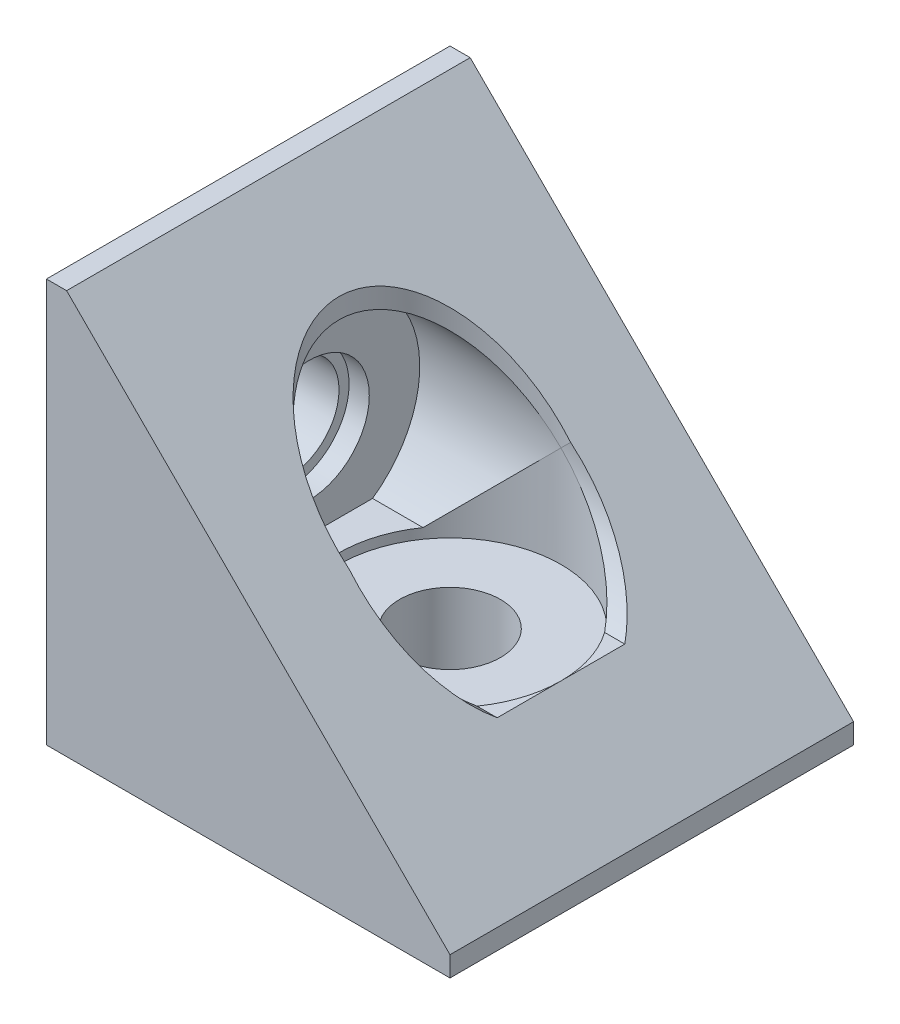
SolidWorks part; units mm, degrees
material "1.4511 (X3CrNb17)"
ref_plane "前视基准面" through (0, 0, 0) normal (0, 0, 1) x (1, 0, 0)
ref_plane "上视基准面" through (0, 0, 0) normal (0, 1, 0) x (1, 0, 0)
ref_plane "右视基准面" through (0, 0, 0) normal (1, 0, 0) x (0, 0, -1)
sketch "草图1" plane through (0, 0, 0) normal (0, 0, 1) x (1, 0, 0)
  line L0 (0, 0) -> (20, 0)
  line L1 (20, 0) -> (20, 1)
  line L2 (20, 1) -> (1, 20)
  line L3 (1, 20) -> (0, 20)
  line L4 (0, 20) -> (0, 0)
  dimension "D1" = 20
  dimension "D2" = 20
  dimension "D3" = 1
  dimension "D4" = 1
extrude "凸台-拉伸1" add sketch "草图1" along normal blind 20
ref_plane "基准面1" through (0, 20, 0) normal (0, 1, 0) x (1, 0, 0)
sketch "草图2" plane through (0, 20, 0) normal (0, 1, 0) x (1, 0, 0)
  line L2 (0, 0) -> (20, -20) construction
  line L3 (20, 0) -> (0, -20) construction
  line L4 (0, -20) -> (0, 0) construction
  line L5 (1, -20) -> (0, -20) construction
  circle A0 centre (10, -10) radius 5.5
  dimension "D1" = 11
extrude "切除-拉伸1" cut sketch "草图2" against normal blind 15
ref_plane "基准面2" through (20, 0, 0) normal (1, 0, 0) x (0, 0, -1)
sketch "草图3" plane through (20, 0, 0) normal (1, 0, 0) x (0, 0, -1)
  line L0 (-20, 20) -> (0, 20) construction
  line L1 (-13.1623, 5.5) -> (-6.8377, 5.5)
  arc A0 (-6.8377, 5.5) -> (-13.1623, 5.5) centre (-10, 10) ccw
  point P7 (-10, 5.5)
  dimension "D1" = 11
  dimension "D2" = 10
extrude "切除-拉伸2" cut sketch "草图3" against normal blind 17
sketch "草图9" plane through (0, 5, 0) normal (0, 1, 0) x (1, 0, 0)
  point P0 (10, -10)
hole_wizard "M6 螺纹孔1" positions "草图10" profile "草图11" tap size "M6" standard "GB" end condition through all
sketch "草图10" plane through (0, 5, 0) normal (0, 1, 0) x (1, 0, 0)
  point P0 (10, -10)
sketch "草图11" plane through (10, 5, 10) normal (1, 0, 0) x (0, 0, 1)
  line L0 (0, 0) -> (0, 5)
  line L1 (0, 5) -> (2.5, 5)
  line L2 (2.5, 5) -> (2.5, 0)
  line L5 (2.5, 0) -> (0, 0)
  line L11 (0, -6.35) -> (0, 107.95) construction
  dimension "通孔螺纹孔钻头直径" = 5
  dimension "通孔螺纹孔钻头深度" = 5
cosmetic thread "孔螺蚊线1" parameters "D2"=6
hole_wizard "打孔尺寸(%根据)内六角圆柱头螺钉的类型1" positions "草图12" profile "草图13" counterbore size "M5" standard "GB"
sketch "草图12" plane through (3, 0, 0) normal (1, 0, 0) x (0, 0, -1)
  point P0 (-10, 10)
sketch "草图13" plane through (3, 10, 10) normal (0, 1, 0) x (0, 0, -1)
  line L0 (0, 0) -> (0, 15.5022)
  line L1 (0, 15.5022) -> (2.5, 14)
  line L2 (2.5, 14) -> (2.5, 1)
  line L3 (2.5, 1) -> (3, 1)
  line L4 (3, 1) -> (3, 0)
  line L5 (3, 0) -> (0, 0)
  line L10 (0, 15.5022) -> (-2.5, 14) construction
  line L11 (0, -6.35) -> (0, 107.95) construction
  dimension "孔直径" = 5
  dimension "孔深度" = 14
  dimension "柱形沉头孔直径" = 6
  dimension "柱形沉头孔深度" = 1
  dimension "导头角度" = 118
